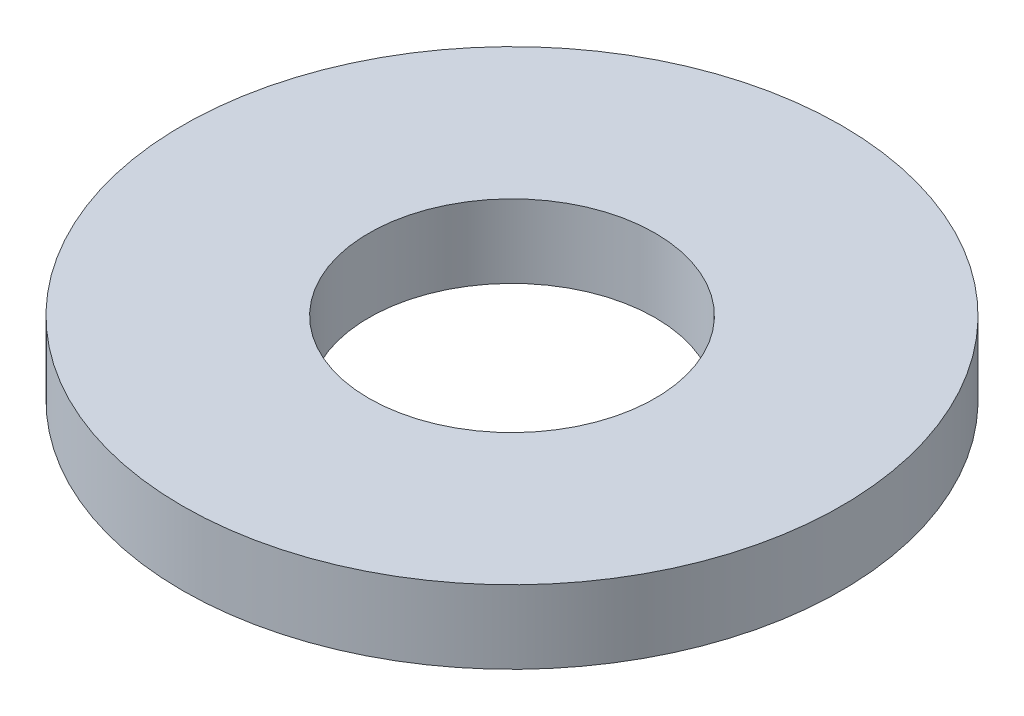
SolidWorks part; units mm, degrees
material "1.0553 (S355J0)"
ref_plane "Front Plane" through (0, 0, 0) normal (0, 0, 1) x (1, 0, 0)
ref_plane "Top Plane" through (0, 0, 0) normal (0, 1, 0) x (1, 0, 0)
ref_plane "Right Plane" through (0, 0, 0) normal (1, 0, 0) x (0, 0, -1)
sketch "Sketch1" plane through (0, 0, 0) normal (0, 1, 0) x (1, 0, 0)
  circle A0 centre (0, 0) radius 24.75
  dimension "D1" = 49.5
extrude "Boss-Extrude1" add sketch "Sketch1" along normal blind 5.5
sketch "Sketch2" plane through (0, 5.5, 0) normal (0, 1, 0) x (1, 0, 0)
  circle A0 centre (0, 0) radius 10.75
  dimension "D1" = 21.5
extrude "Cut-Extrude1" cut sketch "Sketch2" against normal up to next
equation "\"_ulkohalkaisija\" = 49.5"
equation "\"-reiänhalkaisija\" = 21.5"
equation "\"-paksuus\" = 5.5"
equation "\"D1@Sketch1\"= \"_ulkohalkaisija\""
equation "\"D1@Sketch2\"= \"-reiänhalkaisija\""
equation "\"D1@Boss-Extrude1\"= \"-paksuus\""
